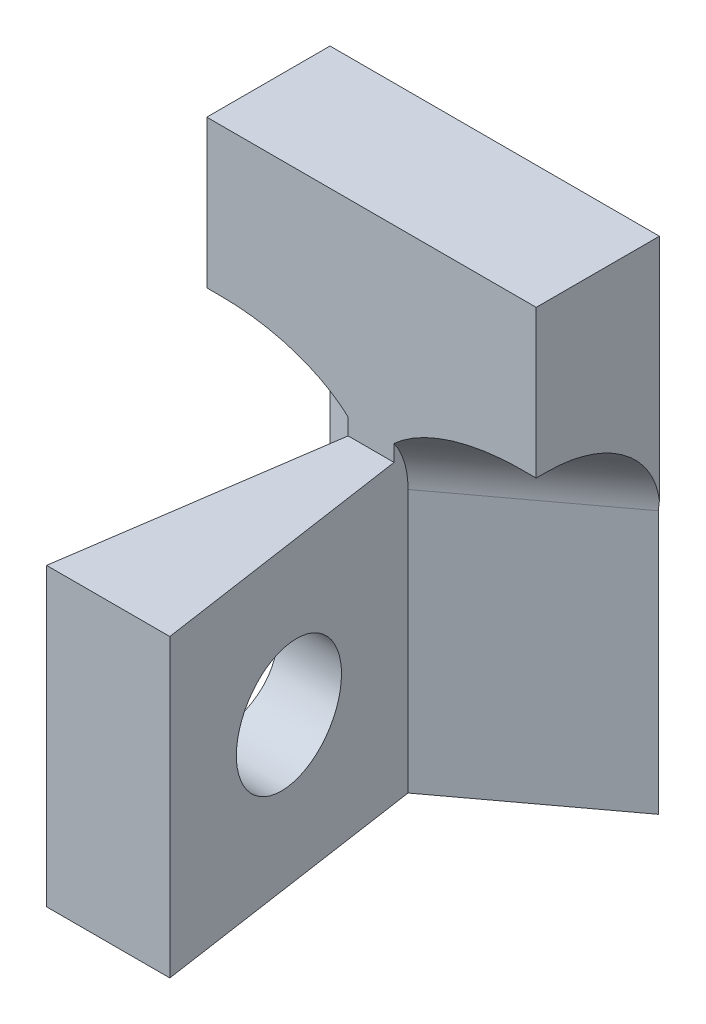
SolidWorks part; units mm, degrees
material "1060 Alloy"
ref_plane "Front Plane" through (0, 0, 0) normal (0, 0, 1) x (1, 0, 0)
ref_plane "Top Plane" through (0, 0, 0) normal (0, 1, 0) x (1, 0, 0)
ref_plane "Right Plane" through (0, 0, 0) normal (1, 0, 0) x (0, 0, -1)
sketch "Sketch1" plane through (0, 0, 0) normal (0, 1, 0) x (1, 0, 0)
  line L0 (20, 0) -> (20, 47) construction
  line L1 (0, 0) -> (40, 0) construction
  line L2 (0, 0) -> (0, 47) construction
  line L3 (0, 47) -> (40, 47) construction
  line L4 (40, 0) -> (40, 47) construction
  line L5 (0, 34) -> (40, 34) construction
  line L6 (27.5, 0) -> (12.5, 0)
  line L7 (12.5, 0) -> (17.5, 34)
  line L8 (22.5, 34) -> (40, 47)
  line L9 (40, 47) -> (0, 47)
  line L10 (27.5, 0) -> (22.5, 34)
  line L11 (0, 47) -> (17.5, 34)
  dimension "D1" = 34
  dimension "D2" = 7.5
  dimension "D3" = 40
  dimension "D4" = 2.5
extrude "Boss-Extrude1" add sketch "Sketch1" along normal blind 36
sketch "Sketch2" plane through (0, 0, 0) normal (1, 0, 0) x (0, 0, -1)
  line L0 (34, 0) -> (0, 0) construction
  line L1 (0, 36) -> (0, 0) construction
  circle A0 centre (17, 18) radius 7.5
  dimension "D1" = 18
  dimension "D3" = 15
  dimension "D2" = 17
extrude "Cut-Extrude1" cut sketch "Sketch2" along normal through all
sketch "Sketch7" plane through (0, 36, 0) normal (0, 1, 0) x (1, 0, 0)
  line L0 (0, 47) -> (40, 47)
  line L1 (40, 47) -> (22.5, 34)
  line L2 (22.5, 34) -> (22.7941, 32)
  line L3 (27.5, 0) -> (22.5, 34) construction
  line L4 (22.7941, 32) -> (17.2059, 32)
  line L5 (17.5, 34) -> (12.5, 0) construction
  line L6 (17.2059, 32) -> (17.5, 34)
  line L7 (17.5, 34) -> (0, 47)
  dimension "D1" = 15
extrude "Boss-Extrude5" add sketch "Sketch7" along normal blind 7
sketch "Sketch9" plane through (0, 43, 0) normal (0, 1, 0) x (1, 0, 0)
  line L1 (0, 47) -> (40.0986, 47)
  line L2 (0, 47) -> (0, 32)
  line L3 (0, 32) -> (40.0986, 32)
  line L4 (40.0986, 47) -> (40.0986, 32)
  dimension "D1" = 15
extrude "Boss-Extrude6" add sketch "Sketch9" along normal blind 18
fillet "Fillet4" radius 11 2 edges at (8.75, 43, -40.5)
